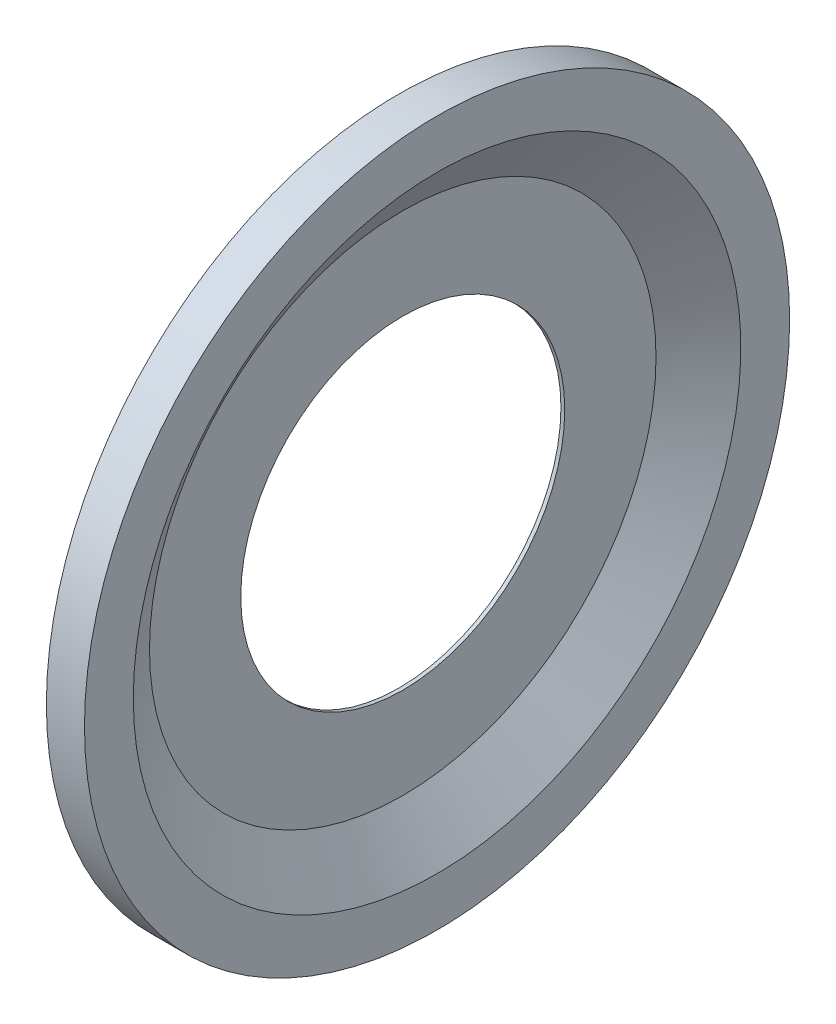
SolidWorks part; units mm, degrees
ref_plane "Plan de face" through (0, 0, 0) normal (0, 0, 1) x (1, 0, 0)
ref_plane "Plan de dessus" through (0, 0, 0) normal (0, 1, 0) x (1, 0, 0)
ref_plane "Plan de droite" through (0, 0, 0) normal (1, 0, 0) x (0, 0, -1)
sketch "Esquisse1" plane through (0, 0, 0) normal (0, 0, 1) x (1, 0, 0)
  line L0 (0, 8.5) -> (0, 13.35)
  line L1 (0, 13.35) -> (1.8, 16)
  line L2 (1.8, 16) -> (1.8, 18.3)
  line L3 (1.8, 18.3) -> (0, 18.3)
  line L4 (-15.7853, 0) -> (14.2068, 0) construction
  dimension "D1" = 17
  dimension "D2" = 26.7
  dimension "D3" = 32
  dimension "D4" = 36.6
  dimension "D5" = 1.8
revolve "Révol.-Mince1" add sketch "Esquisse1" angle 360 about L4
